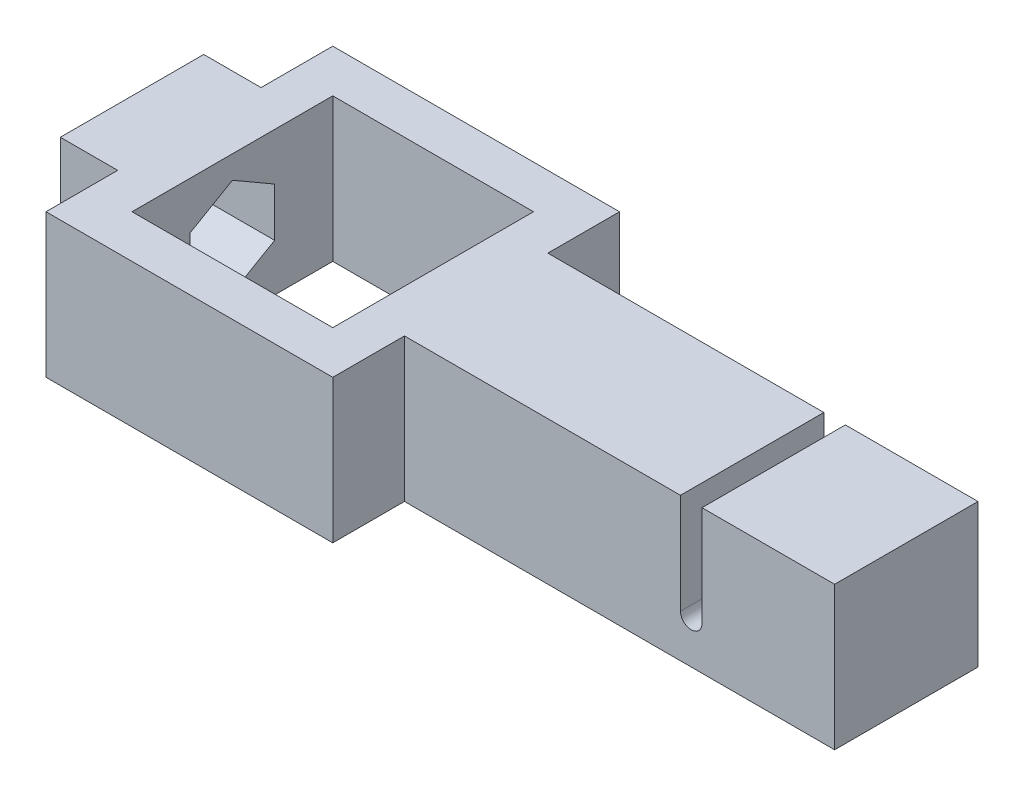
SolidWorks part; units mm, degrees
ref_plane "前视" through (0, 0, 0) normal (0, 0, 1) x (1, 0, 0)
ref_plane "上视" through (0, 0, 0) normal (0, 1, 0) x (1, 0, 0)
ref_plane "右视" through (0, 0, 0) normal (1, 0, 0) x (0, 0, -1)
sketch "Sketch1" plane through (0, 0, 0) normal (0, 1, 0) x (1, 0, 0)
  line L0 (-17, 12) -> (-3, -2) construction
  line L1 (0, 0) -> (30, 0)
  line L2 (0, 0) -> (0, 10) construction
  line L3 (0, 10) -> (30, 10)
  line L4 (30, 0) -> (30, 10)
  line L5 (-20, 10) -> (-24, 10)
  line L6 (-24, 10) -> (-24, 0)
  line L7 (-24, 0) -> (-20, 0)
  line L8 (-20, 10) -> (-20, 15)
  line L9 (-20, 15) -> (0, 15)
  line L10 (0, 15) -> (0, 10)
  line L11 (0, 0) -> (0, -5)
  line L12 (0, -5) -> (-20, -5)
  line L13 (-20, -5) -> (-20, 0)
  line L14 (-17, 12) -> (-3, 12)
  line L15 (-17, 12) -> (-17, -2)
  line L16 (-17, -2) -> (-3, -2)
  line L17 (-3, 12) -> (-3, -2)
  line L18 (0, 15) -> (-20, -5) construction
  point P17 (-10, 5)
  dimension "D1" = 14
  dimension "D4" = 3
  dimension "D2" = 10
  dimension "D3" = 30
  dimension "D5" = 4
  dimension "D6" = 3
extrude "Boss-Extrude1" add sketch "Sketch1" along normal blind 10
sketch "Sketch3" plane through (0, 0, 0) normal (0, 0, 1) x (1, 0, 0)
  line L0 (0, 10) -> (30, 10) construction
  line L1 (19.25, 10) -> (20.75, 10)
  line L2 (19.25, 10) -> (19.25, 3)
  line L3 (19.25, 3) -> (20.75, 3) construction
  line L4 (30, 10) -> (30, 0) construction
  line L5 (20.75, 10) -> (20.75, 3)
  arc A0 (19.25, 3) -> (20.75, 3) centre (20, 3) ccw
  arc A1 (19.25, 3) -> (20.75, 3) centre (20, 3) cw construction
  dimension "D1" = 1.5
  dimension "D2" = 7
  dimension "D3" = 10
extrude "Cut-Extrude1" cut sketch "Sketch3" against normal up to next
sketch "Sketch4" plane through (-24, 0, 0) normal (-1, 0, 0) x (0, 0, 1)
  line L0 (-10, 10) -> (0, 0) construction
  circle A0 centre (-5, 5) radius 1.85
  dimension "D1" = 3.7
extrude "Cut-Extrude2" cut sketch "Sketch4" against normal blind 2
sketch "Sketch5" plane through (-22, 0, 0) normal (-1, 0, 0) x (0, 0, 1)
  line L1 (-5, 8.4) -> (-7.9445, 6.7)
  line L2 (-7.9445, 6.7) -> (-7.9445, 3.3)
  line L3 (-7.9445, 3.3) -> (-5, 1.6)
  line L4 (-5, 1.6) -> (-2.0555, 3.3)
  line L5 (-2.0555, 3.3) -> (-2.0555, 6.7)
  line L6 (-2.0555, 6.7) -> (-5, 8.4)
  circle A0 centre (-5, 5) radius 2.9445 construction
  dimension "D1" = 3.4
extrude "Cut-Extrude3" cut sketch "Sketch5" against normal up to next
